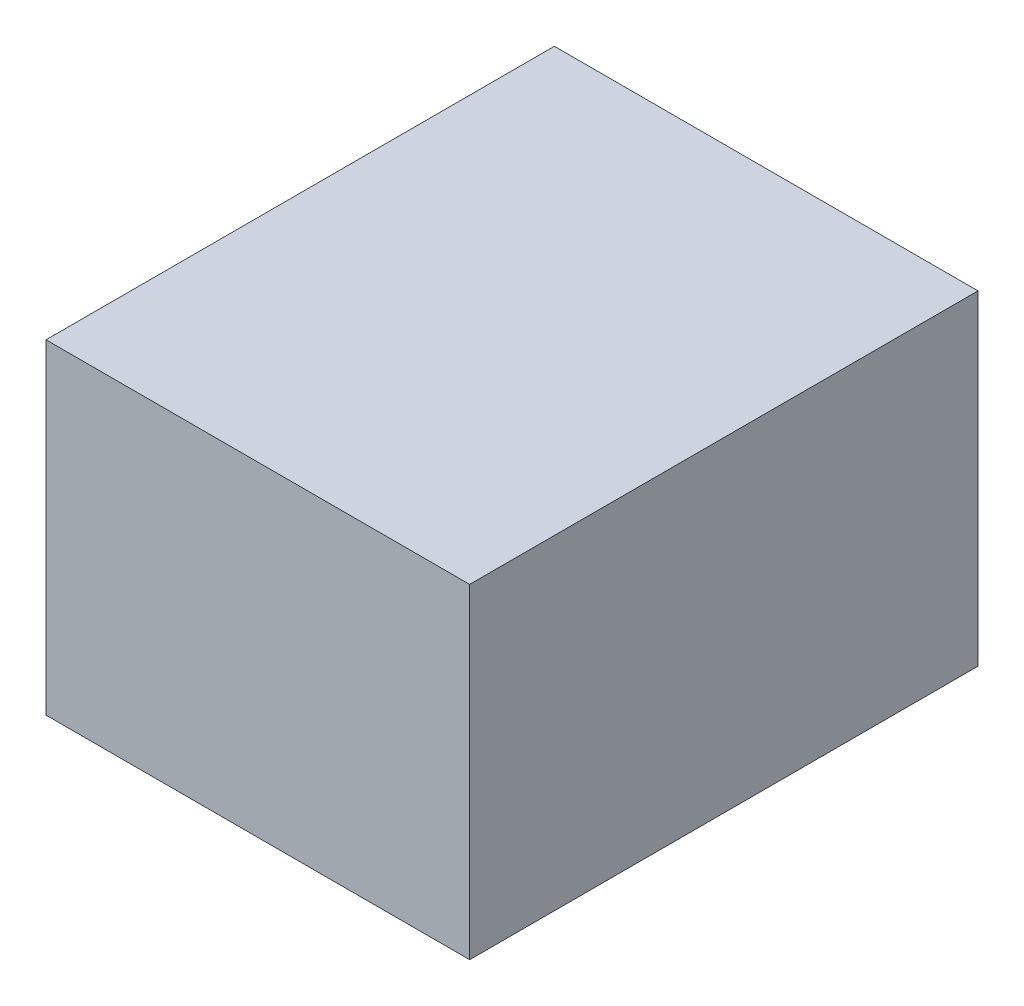
SolidWorks part; units mm, degrees
material "Polyurethane Foam Flexible"
ref_plane "Front Plane" through (0, 0, 0) normal (0, 0, 1) x (1, 0, 0)
ref_plane "Top Plane" through (0, 0, 0) normal (0, 1, 0) x (1, 0, 0)
ref_plane "Right Plane" through (0, 0, 0) normal (1, 0, 0) x (0, 0, -1)
sketch "Sketch1" plane through (0, 0, 0) normal (0, 1, 0) x (1, 0, 0)
  line L1 (0, 0) -> (139.7, 0)
  line L2 (0, 0) -> (0, 167.64)
  line L3 (0, 167.64) -> (139.7, 167.64)
  line L4 (139.7, 0) -> (139.7, 167.64)
  dimension "D1" = 167.64
  dimension "D2" = 139.7
extrude "Boss-Extrude1" add sketch "Sketch1" along normal blind 107.188
